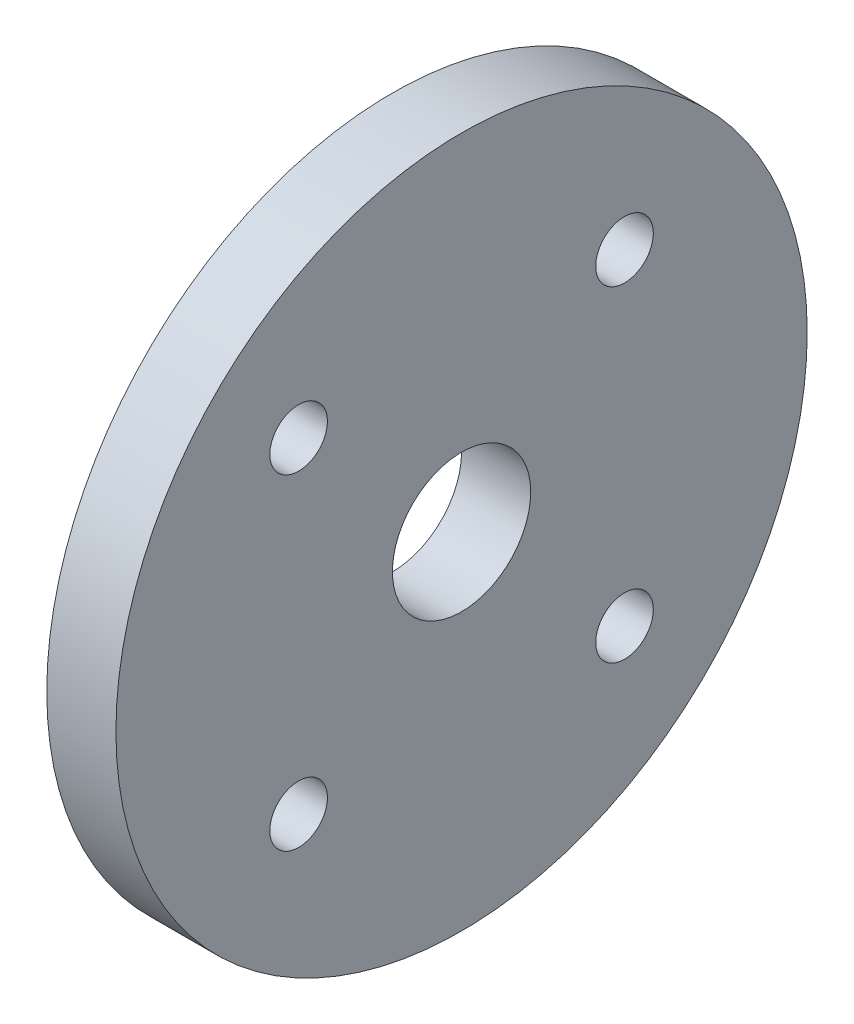
SolidWorks part; units mm, degrees
ref_plane "正面" through (0, 0, 0) normal (0, 0, 1) x (1, 0, 0)
ref_plane "平面" through (0, 0, 0) normal (0, 1, 0) x (1, 0, 0)
ref_plane "右側面" through (0, 0, 0) normal (1, 0, 0) x (0, 0, -1)
sketch "ｽｹｯﾁ1" plane through (0, 0, 0) normal (1, 0, 0) x (0, 0, -1)
  circle A0 centre (0, 0) radius 15
  dimension "D1" = 30
extrude "ﾎﾞｽ - 押し出し1" add sketch "ｽｹｯﾁ1" along normal blind 3
sketch "ｽｹｯﾁ3" plane through (3, 0, 0) normal (1, 0, 0) x (0, 0, -1)
  line L0 (-7.0711, 7.0711) -> (7.0711, -7.0711) construction
  line L1 (-7.0711, 7.0711) -> (7.0711, 7.0711) construction
  line L2 (7.0711, -7.0711) -> (7.0711, 7.0711) construction
  line L3 (-7.0711, 7.0711) -> (-7.0711, -7.0711) construction
  line L4 (-7.0711, -7.0711) -> (7.0711, -7.0711) construction
  line L5 (-7.0711, -7.0711) -> (7.0711, 7.0711) construction
  point P3 (0, 0)
  point P4 (0, 0)
  dimension "D1" = 20
hole_wizard "M3x0.5 ねじ穴1" positions "ｽｹｯﾁ4" profile "ｽｹｯﾁ5" tap size "M3x0.5" standard "JIS" end condition through all
sketch "ｽｹｯﾁ4" plane through (3, 0, 0) normal (1, 0, 0) x (0, 0, -1)
  point P0 (-7.0711, 7.0711)
  point P3 (7.0711, -7.0711)
  point P6 (7.0711, 7.0711)
  point P9 (-7.0711, -7.0711)
sketch "ｽｹｯﾁ5" plane through (3, 7.0711, 7.0711) normal (0, 1, 0) x (0, 0, -1)
  line L0 (0, 0) -> (0, 3)
  line L1 (0, 3) -> (1.25, 3)
  line L2 (1.25, 3) -> (1.25, 0)
  line L5 (1.25, 0) -> (0, 0)
  line L11 (0, -6.35) -> (0, 107.95) construction
  dimension "ねじ山の主要直径" = 2.5
  dimension "次ｻｰﾌｪｽまでのねじ下穴ﾄﾞﾘﾙの深さ" = 3
sketch "ｽｹｯﾁ6" plane through (3, 0, 0) normal (1, 0, 0) x (0, 0, -1)
  circle A0 centre (0, 0) radius 3
  dimension "D1" = 6
extrude "ｶｯﾄ - 押し出し2" cut sketch "ｽｹｯﾁ6" against normal through all
